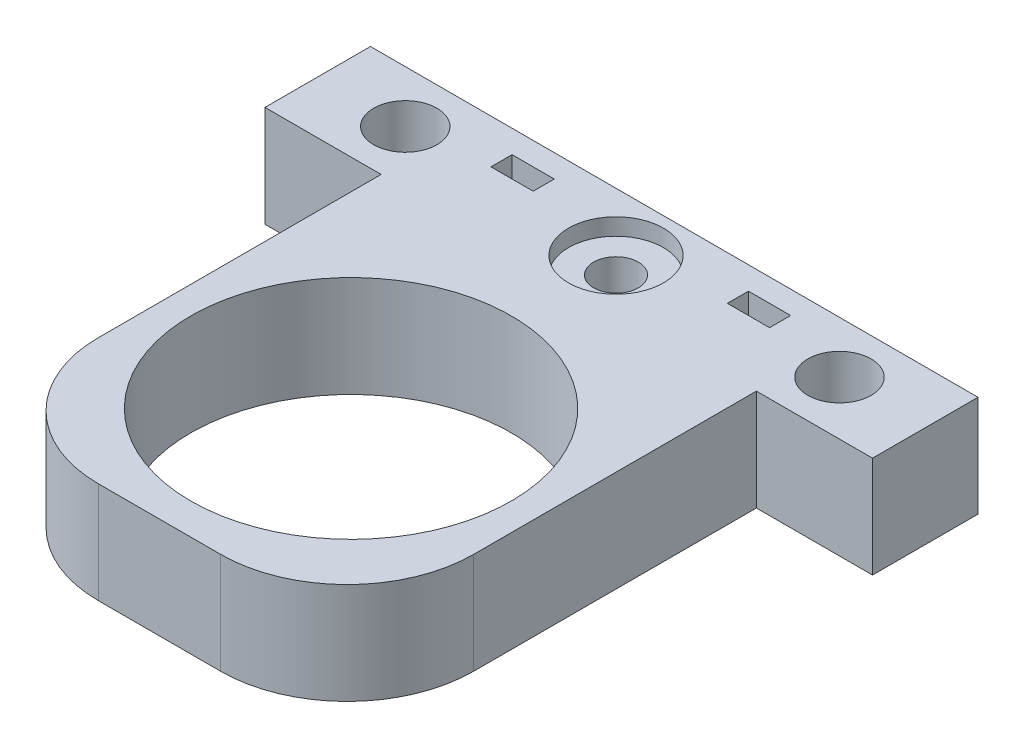
SolidWorks part; units mm, degrees
ref_plane "Front Plane" through (0, 0, 0) normal (0, 0, 1) x (1, 0, 0)
ref_plane "Top Plane" through (0, 0, 0) normal (0, 1, 0) x (1, 0, 0)
ref_plane "Right Plane" through (0, 0, 0) normal (1, 0, 0) x (0, 0, -1)
sketch "Sketch1" plane through (0, 0, 0) normal (0, 1, 0) x (1, 0, 0)
  line L0 (0, 0) -> (0, -45) construction
  line L1 (-65, 25) -> (65, 25)
  line L2 (-65, 25) -> (-65, -25)
  line L3 (-65, -25) -> (-32.8976, -25)
  line L4 (65, 25) -> (65, -25)
  line L5 (-65, 25) -> (65, -25) construction
  line L6 (-65, -25) -> (65, 25) construction
  line L7 (32.8976, -25) -> (65, -25)
  arc A0 (32.8976, -25) -> (-32.8976, -25) centre (0, -45) ccw
  point P0 (0, 0)
  dimension "D4" = 77
  dimension "D1" = 50
  dimension "D2" = 130
  dimension "D3" = 45
extrude "Boss-Extrude1" add sketch "Sketch1" along normal blind 60
sketch "Sketch2" plane through (0, 60, 0) normal (0, 1, 0) x (1, 0, 0)
  line L0 (0, -6.5) -> (0, 25) construction
  line L1 (65, 25) -> (-65, 25) construction
  circle A0 centre (-51.4526, 12.7142) radius 7.5
  arc A1 (32.8976, -25) -> (-32.8976, -25) centre (0, -45) ccw construction
  circle A2 centre (51.4526, 12.7142) radius 7.5
  dimension "D1" = 15
extrude "Cut-Extrude1" cut sketch "Sketch2" against normal blind 60
sketch "Sketch3" plane through (0, 60, 0) normal (0, 1, 0) x (1, 0, 0)
  line L0 (0, -6.5) -> (0, 25) construction
  line L1 (65, 25) -> (-65, 25) construction
  line L2 (-51.4526, 12.7142) -> (51.4526, 12.7142) construction
  arc A0 (32.8976, -25) -> (-32.8976, -25) centre (0, -45) ccw construction
  circle A1 centre (0, 12.7142) radius 5.25
  dimension "D1" = 10.5
extrude "Cut-Extrude2" cut sketch "Sketch3" against normal blind 60
sketch "Sketch4" plane through (0, 60, 0) normal (0, 1, 0) x (1, 0, 0)
  circle A0 centre (0, 12.7142) radius 11.5
  dimension "D1" = 23
extrude "Cut-Extrude3" cut sketch "Sketch4" against normal blind 4
sketch "Sketch5" plane through (0, 60, 0) normal (0, 1, 0) x (1, 0, 0)
  line L0 (0, 25) -> (0, -6.5) construction
  line L1 (-57.8842, -14.0803) -> (-47.8842, -14.0803)
  line L2 (-57.8842, -14.0803) -> (-57.8842, -19.0803)
  line L3 (-57.8842, -19.0803) -> (-47.8842, -19.0803)
  line L4 (-47.8842, -14.0803) -> (-47.8842, -19.0803)
  line L5 (65, 25) -> (-65, 25) construction
  line L6 (-33.0131, 19.5794) -> (-23.0131, 19.5794)
  line L7 (-33.0131, 19.5794) -> (-33.0131, 14.5794)
  line L8 (-33.0131, 14.5794) -> (-23.0131, 14.5794)
  line L9 (-23.0131, 19.5794) -> (-23.0131, 14.5794)
  line L10 (57.8842, -19.0803) -> (47.8842, -19.0803)
  line L11 (47.8842, -14.0803) -> (47.8842, -19.0803)
  line L12 (57.8842, -14.0803) -> (47.8842, -14.0803)
  line L13 (57.8842, -14.0803) -> (57.8842, -19.0803)
  line L14 (33.0131, 19.5794) -> (33.0131, 14.5794)
  line L15 (33.0131, 14.5794) -> (23.0131, 14.5794)
  line L16 (23.0131, 19.5794) -> (23.0131, 14.5794)
  line L17 (33.0131, 19.5794) -> (23.0131, 19.5794)
  arc A0 (32.8976, -25) -> (-32.8976, -25) centre (0, -45) ccw construction
  dimension "D1" = 5
  dimension "D2" = 10
extrude "Cut-Extrude4" cut sketch "Sketch5" against normal blind 60
sketch "Sketch6" plane through (0, 60, 0) normal (0, 1, 0) x (1, 0, 0)
  line L0 (-65, 25) -> (-65, -25) construction
  line L1 (-65, 0) -> (65, 0)
  line L2 (-65, 0) -> (-65, -90)
  line L3 (-65, -90) -> (65, -90)
  line L4 (65, 0) -> (65, -90)
  dimension "D1" = 90
extrude "Boss-Extrude2" add sketch "Sketch6" against normal blind 60
sketch "Sketch7" plane through (0, 60, 0) normal (0, 1, 0) x (1, 0, 0)
  line L0 (0, 12.7142) -> (0, -51.2858) construction
  circle A0 centre (0, -51.2858) radius 38.5
  dimension "D2" = 77
  dimension "D1" = 64
sketch "Sketch8" plane through (0, 0, 0) normal (0, -1, 0) x (1, 0, 0)
  line L1 (-65, 90) -> (65, 90)
  line L2 (-65, 90) -> (-65, -25)
  line L3 (-65, -25) -> (65, -25)
  line L4 (65, 90) -> (65, -25)
extrude "Cut-Extrude6" cut sketch "Sketch8" against normal blind 20
sketch "Sketch9" plane through (0, 60, 0) normal (0, 1, 0) x (1, 0, 0)
  line L0 (-65, 25) -> (-65, -90) construction
  line L1 (-65, 0) -> (-44.4744, 0)
  line L2 (-65, 0) -> (-65, -90)
  line L3 (-65, -90) -> (-44.4744, -90)
  line L4 (-44.4744, 0) -> (-44.4744, -90)
  line L5 (-65, -90) -> (65, -90) construction
  line L6 (0, 12.7142) -> (0, -90) construction
  line L7 (65, -90) -> (44.4744, -90)
  line L8 (44.4744, 0) -> (44.4744, -90)
  line L9 (65, 0) -> (44.4744, 0)
  line L10 (65, 0) -> (65, -90)
extrude "Cut-Extrude7" cut sketch "Sketch9" against normal blind 45
extrude "Cut-Extrude8" cut sketch "Sketch7" against normal blind 40
sketch "Sketch12" plane through (0, 0, 90) normal (0, 0, 1) x (1, 0, 0)
  line L1 (-44.4744, 60) -> (44.4744, 60)
  line L2 (-44.4744, 60) -> (-44.4744, 20)
  line L3 (-44.4744, 20) -> (44.4744, 20)
  line L4 (44.4744, 60) -> (44.4744, 20)
extrude "Boss-Extrude4" add sketch "Sketch12" along normal blind 7
sketch "Sketch13" plane through (65, 0, 0) normal (1, 0, 0) x (0, 0, -1)
  line L1 (0, 60) -> (25, 60)
  line L2 (0, 60) -> (0, 20)
  line L3 (0, 20) -> (25, 20)
  line L4 (25, 60) -> (25, 20)
extrude "Boss-Extrude5" add sketch "Sketch13" along normal blind 7
sketch "Sketch14" plane through (-65, 0, 0) normal (-1, 0, 0) x (0, 0, 1)
  line L1 (-25, 60) -> (0, 60)
  line L2 (-25, 60) -> (-25, 20)
  line L3 (-25, 20) -> (0, 20)
  line L4 (0, 60) -> (0, 20)
extrude "Boss-Extrude6" add sketch "Sketch14" along normal blind 7
sketch "Sketch15" plane through (-44.4744, 0, 0) normal (-1, 0, 0) x (0, 0, 1)
  line L0 (97, 60) -> (97, 20) construction
sketch "Sketch16" plane through (0, 60, 0) normal (0, 1, 0) x (1, 0, 0)
  line L1 (-72, 25) -> (72.2963, 25)
  line L2 (-72, 25) -> (-72, -97.2488)
  line L3 (-72, -97.2488) -> (72.2963, -97.2488)
  line L4 (72.2963, 25) -> (72.2963, -97.2488)
extrude "Cut-Extrude9" cut sketch "Sketch16" against normal blind 16
sketch "Sketch23" plane through (0, 44, 0) normal (0, 1, 0) x (1, 0, 0)
  circle A2 centre (0, 12.7142) radius 10.5749
extrude "Boss-Extrude7" add sketch "Sketch23" against normal blind 24
sketch "Sketch24" plane through (0, 44, 0) normal (0, 1, 0) x (1, 0, 0)
  line L0 (0, 25) -> (0, 11.2) construction
  line L1 (72, 25) -> (-72, 25) construction
  circle A0 centre (0, 11.2) radius 5.3
  dimension "D2" = 10.6
  dimension "D1" = 13.8
extrude "Cut-Extrude11" cut sketch "Sketch24" against normal blind 24
sketch "Sketch25" plane through (0, 44, 0) normal (0, 1, 0) x (1, 0, 0)
  circle A1 centre (0, 11.2) radius 11.25
  dimension "D1" = 22.5
extrude "Cut-Extrude12" cut sketch "Sketch25" against normal blind 4
sketch "Sketch26" plane through (0, 44, 0) normal (0, 1, 0) x (1, 0, 0)
  line L0 (0, -12.7858) -> (0, -89.7858) construction
  circle A0 centre (0, -51.2858) radius 38.5 construction
  circle A1 centre (0, -51.2858) radius 41.2415
extrude "Boss-Extrude8" add sketch "Sketch26" against normal blind 24
sketch "Sketch27" plane through (0, 44, 0) normal (0, 1, 0) x (1, 0, 0)
  circle A0 centre (0, -51.5965) radius 38
  dimension "D1" = 76
extrude "Cut-Extrude13" cut sketch "Sketch27" against normal blind 24
fillet "Fillet2" radius 30 2 edges at (-44.4744, 32, 97) (44.4744, 32, 97)
